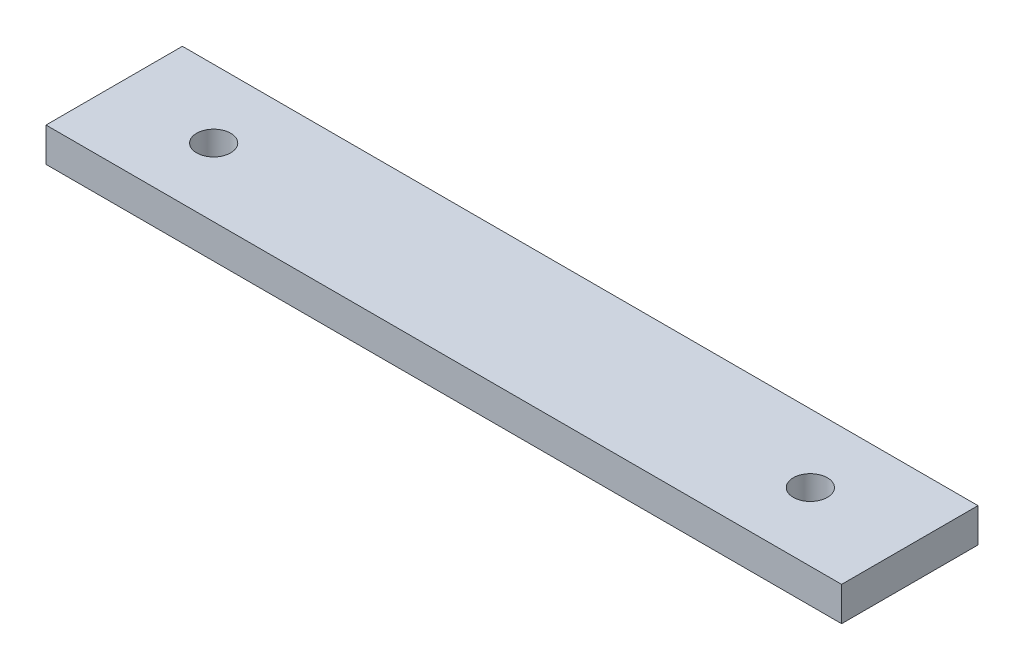
SolidWorks part; units mm, degrees
ref_plane "Front Plane" through (0, 0, 0) normal (0, 0, 1) x (1, 0, 0)
ref_plane "Top Plane" through (0, 0, 0) normal (0, 1, 0) x (1, 0, 0)
ref_plane "Right Plane" through (0, 0, 0) normal (1, 0, 0) x (0, 0, -1)
sketch "Sketch1" plane through (0, 0, 0) normal (0, 1, 0) x (1, 0, 0)
  line L1 (-35, -6) -> (35, -6)
  line L2 (-35, -6) -> (-35, 6)
  line L3 (-35, 6) -> (35, 6)
  line L4 (35, -6) -> (35, 6)
  line L5 (-35, -6) -> (35, 6) construction
  line L6 (-35, 6) -> (35, -6) construction
  point P0 (0, 0)
  dimension "D1" = 12
extrude "Boss-Extrude1" add sketch "Sketch1" along normal blind 3
sketch "Sketch3" plane through (0, 3, 0) normal (0, 1, 0) x (1, 0, 0)
  line L0 (-26.25, 0) -> (26.25, 0) construction
  circle A0 centre (-26.25, 0) radius 1.5
  circle A1 centre (26.25, 0) radius 1.5
  point P5 (0, 0)
  dimension "D1" = 1.5
  dimension "D2" = 52.5
extrude "Cut-Extrude1" cut sketch "Sketch3" against normal through all contours A1 | A0
sketch "Sketch4" plane through (0, 0, 0) normal (0, -1, 0) x (1, 0, 0)
  circle A0 centre (0, 0) radius 5
  dimension "D1" = 5
